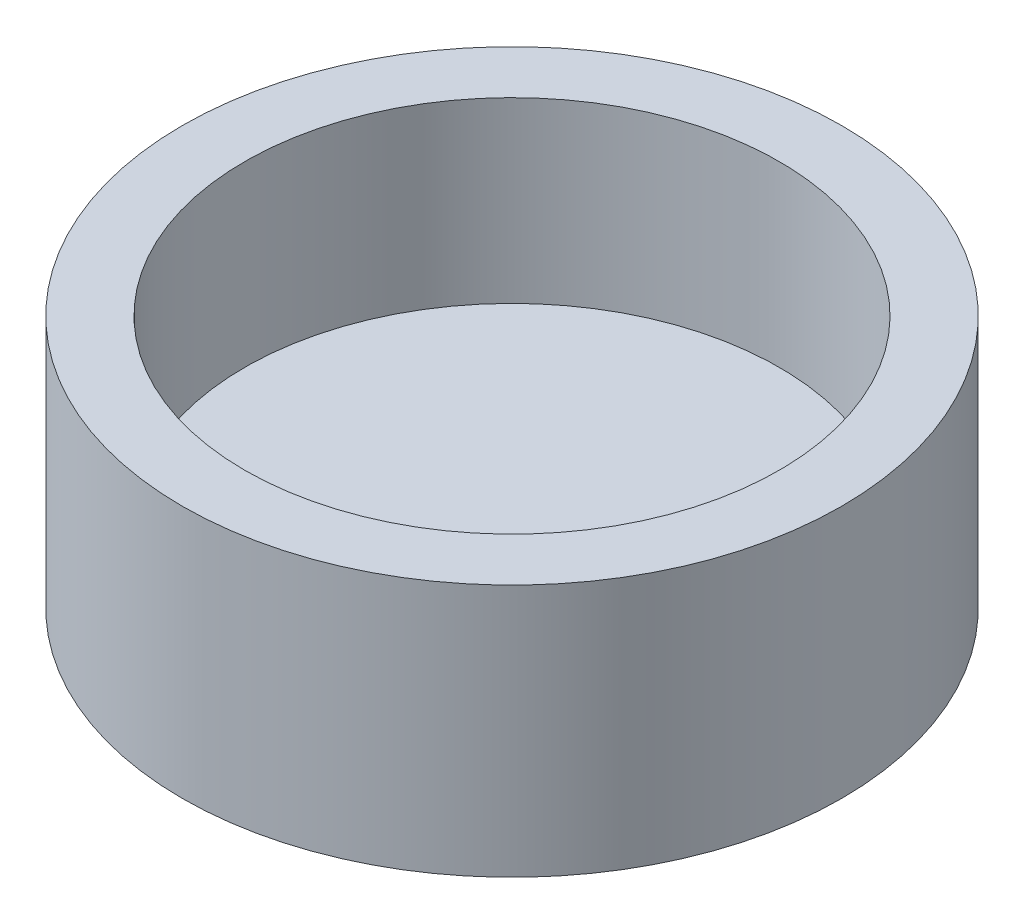
SolidWorks part; units mm, degrees
ref_plane "Front Plane" through (0, 0, 0) normal (0, 0, 1) x (1, 0, 0)
ref_plane "Top Plane" through (0, 0, 0) normal (0, 1, 0) x (1, 0, 0)
ref_plane "Right Plane" through (0, 0, 0) normal (1, 0, 0) x (0, 0, -1)
sketch "Sketch1" plane through (0, 0, 0) normal (0, 1, 0) x (1, 0, 0)
  circle A0 centre (0, 0) radius 9.25
  dimension "D1" = 18.5
extrude "Boss-Extrude1" add sketch "Sketch1" along normal blind 7.1
sketch "Sketch2" plane through (0, 7.1, 0) normal (0, 1, 0) x (1, 0, 0)
  circle A0 centre (0, 0) radius 7.5
  dimension "D1" = 15
extrude "Cut-Extrude1" cut sketch "Sketch2" against normal blind 5
